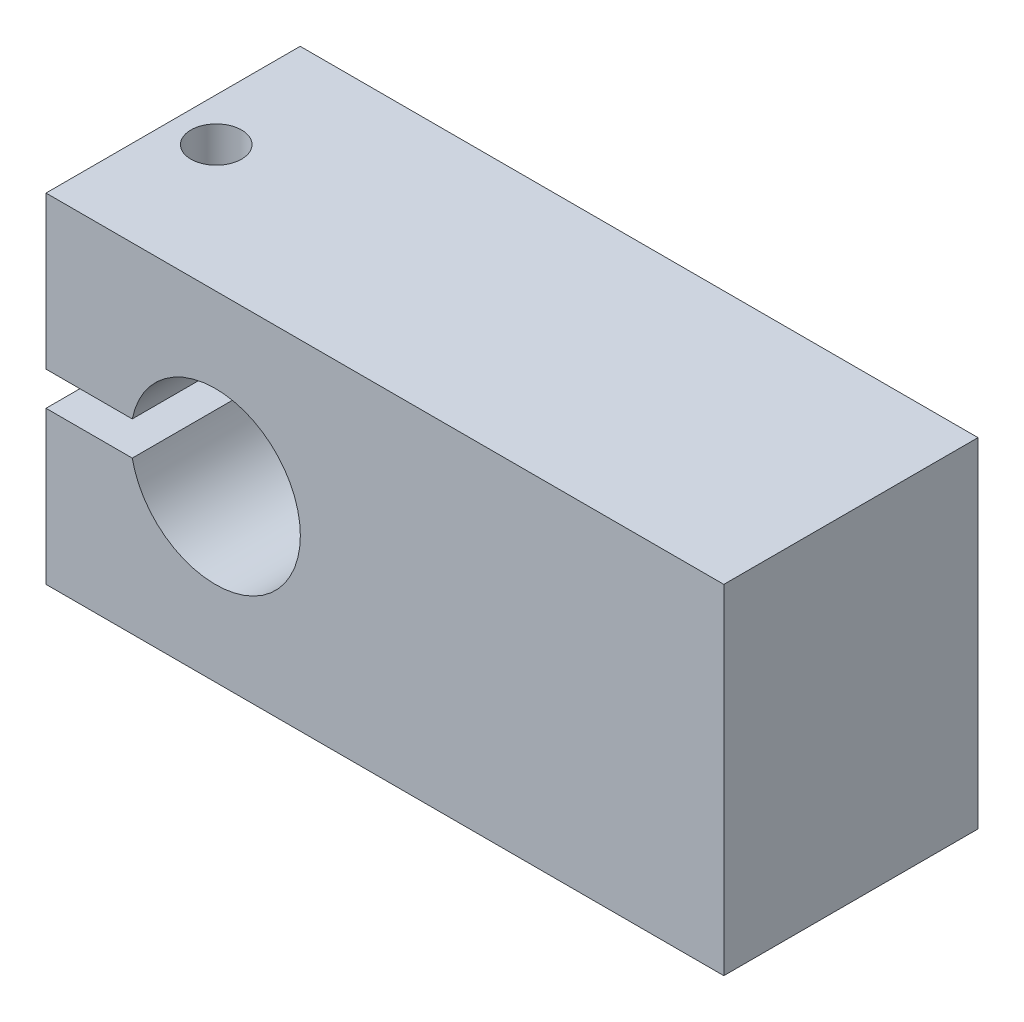
SolidWorks part; units mm, degrees
ref_plane "Front Plane" through (0, 0, 0) normal (0, 0, 1) x (1, 0, 0)
ref_plane "Top Plane" through (0, 0, 0) normal (0, 1, 0) x (1, 0, 0)
ref_plane "Right Plane" through (0, 0, 0) normal (1, 0, 0) x (0, 0, -1)
sketch "Sketch1" plane through (0, 0, 0) normal (0, 0, 1) x (1, 0, 0)
  line L1 (0, 0) -> (50.8, 0)
  line L2 (0, 0) -> (0, 25.4)
  line L3 (0, 25.4) -> (50.8, 25.4)
  line L4 (50.8, 0) -> (50.8, 25.4)
  dimension "D1" = 50.8
  dimension "D2" = 25.4
extrude "Boss-Extrude1" add sketch "Sketch1" along normal blind 19.05
sketch "Sketch2" plane through (0, 0, 19.05) normal (0, 0, 1) x (1, 0, 0)
  line L0 (0, 12.7) -> (12.7, 12.7) construction
  line L1 (0, 25.4) -> (0, 0) construction
  line L3 (12.7, 11.43) -> (0, 11.43)
  line L4 (12.7, 11.43) -> (12.7, 13.97)
  line L5 (12.7, 13.97) -> (0, 13.97)
  line L6 (0, 11.43) -> (0, 13.97)
  line L7 (12.7, 11.43) -> (0, 13.97) construction
  line L8 (12.7, 13.97) -> (0, 11.43) construction
  circle A0 centre (12.7, 12.7) radius 6.3627
  point P3 (6.35, 12.7)
  line M7 (0, 25.4) -> (0, 0)
  dimension "D1" = 12.7254
  dimension "D2" = 2.54
  dimension "D3" = 12.7
extrude "Cut-Extrude1" cut sketch "Sketch2" against normal blind 19.05 contours L3 A0 L5 L4 | A0 L5 L3 M7 | L5 A0 L3 L4
hole_wizard "#6 Clearance Hole1" positions "Sketch3" profile "Sketch4" hole size "#6" standard "ANSI Inch"
sketch "Sketch3" plane through (0, 25.4, 0) normal (0, 1, 0) x (1, 0, 0)
  line L0 (0, -9.525) -> (6.4653, -9.525) construction
  line L1 (0, -19.05) -> (0, 0) construction
  line L2 (6.4653, 0) -> (6.4653, -19.05) construction
  point P9 (3.2327, -9.525)
sketch "Sketch4" plane through (3.2327, 25.4, 9.525) normal (1, 0, 0) x (0, 0, 1)
  line L0 (0, 0) -> (0, 11.43)
  line L1 (0, 11.43) -> (1.8986, 11.43)
  line L2 (1.8986, 11.43) -> (1.8986, 0)
  line L5 (1.8986, 0) -> (0, 0)
  line L11 (0, -6.35) -> (0, 107.95) construction
  dimension "Thru Hole Dia." = 3.7973
  dimension "Thru Hole Depth" = 11.43
hole_wizard "#6-32 Tapped Hole1" positions "Sketch5" profile "Sketch6" tap size "#6-32" standard "ANSI Inch" end condition up to next
sketch "Sketch5" plane through (0, 11.43, 0) normal (0, 1, 0) x (1, 0, 0)
  point P0 (3.2327, -9.525)
sketch "Sketch6" plane through (3.2327, 11.43, 9.525) normal (1, 0, 0) x (0, 0, 1)
  line L0 (0, 0) -> (0, 11.43)
  line L1 (0, 11.43) -> (1.3525, 11.43)
  line L2 (1.3525, 11.43) -> (1.3525, 0)
  line L5 (1.3525, 0) -> (0, 0)
  line L11 (0, -6.35) -> (0, 107.95) construction
  dimension "Thru Tap Drill Dia." = 2.7051
  dimension "Thru Tap Drill Depth" = 11.43
cosmetic thread "Hole Thread1" parameters "D2"=3.5052
